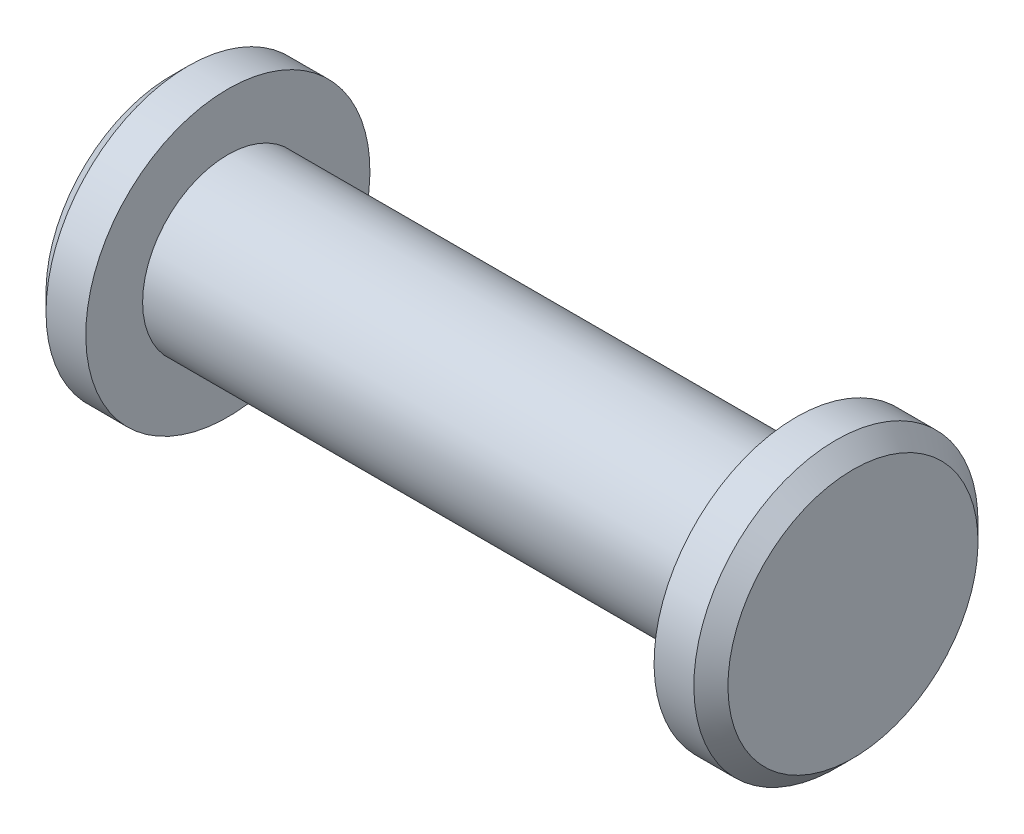
SolidWorks part; units mm, degrees
ref_plane "Front Plane" through (0, 0, 0) normal (0, 0, 1) x (1, 0, 0)
ref_plane "Top Plane" through (0, 0, 0) normal (0, 1, 0) x (1, 0, 0)
ref_plane "Right Plane" through (0, 0, 0) normal (1, 0, 0) x (0, 0, -1)
sketch "Sketch1" plane through (0, 0, 0) normal (0, 0, 1) x (1, 0, 0)
  line L0 (0, 0) -> (-120, 0)
  line L1 (-120, 0) -> (-120, 25)
  line L2 (-120, 25) -> (-110, 25)
  line L3 (-110, 25) -> (-110, 15)
  line L4 (-110, 15) -> (-10, 15)
  line L5 (-10, 15) -> (-10, 25)
  line L6 (-10, 25) -> (0, 25)
  line L7 (0, 25) -> (0, 0)
  dimension "D1" = 100
  dimension "D2" = 10
  dimension "D3" = 10
  dimension "D4" = 15
  dimension "D5" = 25
revolve "Revolve1" add sketch "Sketch1" angle 360 about L0
chamfer "Chamfer1" distance 3 angle 45 2 edges at (0, 25, 0) (-120, 25, 0)
